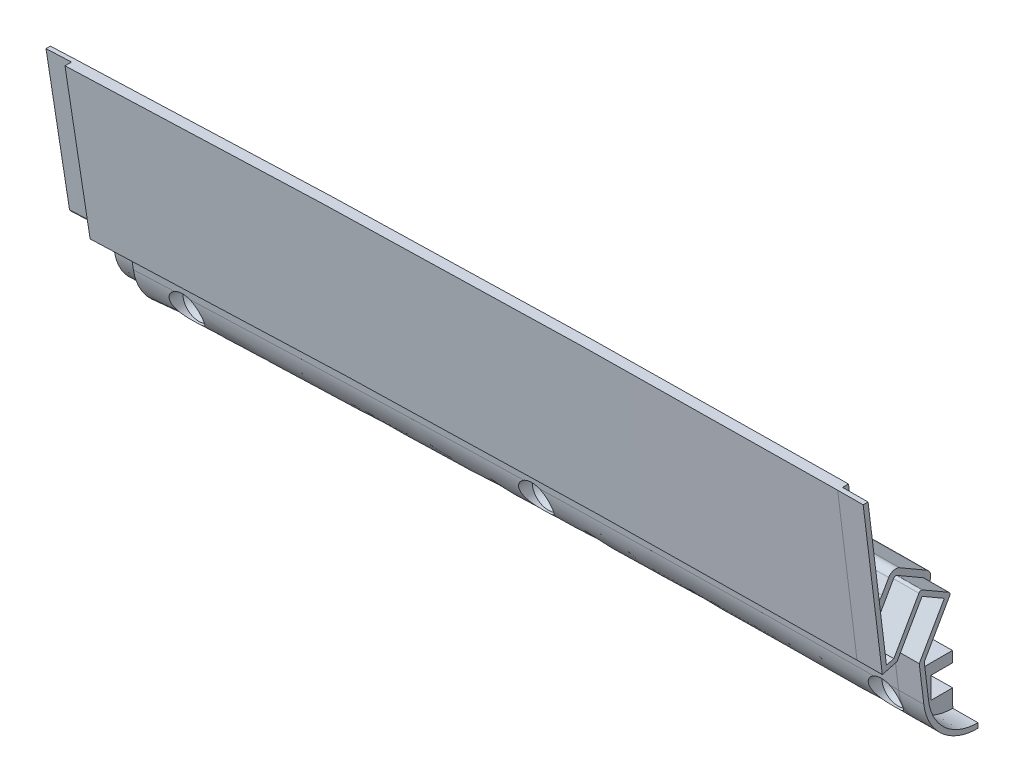
SolidWorks part; units mm, degrees
ref_plane "Front Plane" through (0, 0, 0) normal (0, 0, 1) x (1, 0, 0)
ref_plane "Top Plane" through (0, 0, 0) normal (0, 1, 0) x (1, 0, 0)
ref_plane "Right Plane" through (0, 0, 0) normal (1, 0, 0) x (0, 0, -1)
ref_plane "Plane3" through (-117.056, -3.871, 0) normal (0.9995, 0.0331, 0) x (0, 0, -1)
sketch "Sketch2" plane through (-117.056, -3.871, 0) normal (0.9995, 0.0331, 0) x (0, 0, -1)
  line L0 (-101.6, -41.1511) -> (-101.6, -45.9265)
  line L1 (-101.6, -41.1511) -> (-101.6, -45.9265)
  line L2 (-106.68, -45.9265) -> (-106.68, -50.6257)
  line L3 (-106.68, -45.9265) -> (-106.68, -50.6257)
  line L4 (-101.6, -50.6257) -> (-106.68, -50.6257)
  line L5 (-101.6, -50.6257) -> (-106.68, -50.6257)
  line L6 (-101.6, -50.6257) -> (-101.6, -56.1377)
  line L7 (-101.6, -50.6257) -> (-101.6, -56.1377)
  line L8 (-106.68, -45.9265) -> (-101.6, -45.9265)
  line L9 (-106.68, -45.9265) -> (-101.6, -45.9265)
  line L10 (-106.8705, -50.8162) -> (-108.9961, -53.9781) construction
  line L11 (-101.7905, -43.196) -> (-101.7905, -45.736)
  line L12 (-106.8705, -45.736) -> (-101.7905, -45.736)
  line L13 (-106.8705, -45.736) -> (-106.8705, -50.8162)
  line L14 (-101.7905, -50.8162) -> (-106.8705, -50.8162)
  line L15 (-101.7905, -50.8162) -> (-101.7905, -56.1377)
  line L16 (-101.7905, -43.196) -> (-101.6, -43.196)
  line L17 (-101.7905, -41.1511) -> (-101.7905, -45.736) construction
  line L18 (-120.8053, -33.0481) -> (-115.57, -36.0708)
  line L19 (-120.8053, -33.0481) -> (-115.57, -36.0708)
  line L20 (-109.601, -25.7318) -> (-114.8363, -22.709)
  line L21 (-109.601, -25.7318) -> (-114.8363, -22.709)
  line L22 (-114.8363, -22.709) -> (-120.8053, -33.0481)
  line L23 (-114.8363, -22.709) -> (-120.8053, -33.0481)
  line L24 (-115.57, -36.0708) -> (-109.601, -25.7318)
  line L25 (-115.57, -36.0708) -> (-109.601, -25.7318)
  line L26 (-115.57, -36.0708) -> (-114.523, -44.9291)
  line L28 (-118.1876, -34.5595) -> (-112.2186, -24.2204) construction
  line L29 (-114.6403, -39.5406) -> (-107.0838, -26.4518)
  line L30 (-107.7811, -23.8496) -> (-114.1162, -20.1918)
  line L31 (-116.7185, -20.8891) -> (-124.2749, -33.9778)
  line L33 (-106.1314, -24.8021) -> (-115.766, -19.2393) construction
  line L34 (-115.766, -19.2393) -> (-124.2749, -33.9778) construction
  line L35 (-114.6403, -39.5406) -> (-106.1314, -24.8021) construction
  line L36 (-124.2749, -33.9778) -> (-114.6403, -39.5406) construction
  line L37 (-112.9486, -36.6103) -> (-112.1701, -43.196)
  line L38 (-124.2749, -33.9778) -> (-128.0422, -2.1051)
  line L39 (-128.0422, -2.1051) -> (-132.6063, -0.4439)
  line L40 (-50.8, 0.7495) -> (-2184.4, 0.7495)
  line L41 (-125.822, 0.7495) -> (-133.442, 0.7495)
  line L42 (-122.1519, -30.3004) -> (-125.822, 0.7495)
  arc A0 (-114.523, -44.9291) -> (-101.7905, -56.1377) centre (-101.9108, -43.4383) ccw
  arc A2 (-114.1162, -20.1918) -> (-116.7185, -20.8891) centre (-115.0687, -21.8416) ccw
  arc A3 (-107.0838, -26.4518) -> (-107.7811, -23.8496) centre (-108.7336, -25.4993) ccw
  arc A4 (-133.442, 0.7495) -> (-132.6063, -0.4439) centre (-132.172, 0.7495) ccw
  point P41 (-133.442, 0.7495)
  dimension "D2" = 25.4
  dimension "D6" = 1.905
  dimension "D8" = 2.54
  dimension "D4" = 2.54
  dimension "D5" = 2.54
  dimension "D7" = 2.54
  dimension "D9" = 2.54
  dimension "D10" = 20
  dimension "D11" = 7.62
  dimension "D12" = 3.81
  dimension "D3" = 0.1905
sketch "Sketch3" plane through (0, 0, 101.6) normal (0, 0, 1) x (1, 0, 0)
  arc A0 (622.1039, -83.1998) -> (-622.1039, -83.1998) centre (0, -4954.4862) ccw construction
  arc A1 (622.1039, -83.1998) -> (-622.1039, -83.1998) centre (0, -4954.4862) ccw
sketch "Sketch4" plane through (-117.3306, 4.4304, 1117.6) normal (0.9995, 0.0331, 0) x (0, 0, -1)
  line L29 (1009.8189, -32.1556) -> (1003.4838, -28.4978) construction
  line L32 (1000.8815, -29.1951) -> (993.3251, -42.2838) construction
  line L35 (993.3251, -42.2838) -> (989.5578, -10.4111) construction
  line L50 (995.4481, -38.6064) -> (991.778, -7.5565) construction
  line L51 (1002.03, -44.3768) -> (1003.077, -53.235) construction
  line L52 (1015.8095, -59.1222) -> (1015.8095, -64.4437) construction
  line L53 (1015.8095, -59.1222) -> (1010.7295, -59.1222) construction
  line L54 (1010.7295, -54.042) -> (1010.7295, -59.1222) construction
  line L55 (1010.7295, -54.042) -> (1015.8095, -54.042) construction
  line L56 (1015.8095, -51.502) -> (1015.8095, -54.042) construction
  line L57 (1015.8095, -51.502) -> (1016, -51.502) construction
  line L58 (1004.6514, -44.9163) -> (1005.4299, -51.502) construction
  line L60 (1002.7637, -31.015) -> (996.7947, -41.3541) construction
  line L61 (1007.999, -34.0377) -> (1002.7637, -31.015) construction
  line L62 (1002.03, -44.3768) -> (1007.999, -34.0377) construction
  line L64 (991.5295, -5.4538) -> (988.9718, -5.4538)
  line L69 (1009.8189, -32.1556) -> (1003.4838, -28.4978)
  line L70 (1000.8815, -29.1951) -> (999.2724, -31.9822)
  line L71 (993.3251, -42.2838) -> (988.9718, -5.4538)
  line L74 (994.5502, -31.0104) -> (991.5295, -5.4538)
  line L75 (1002.03, -44.3768) -> (1003.077, -53.235)
  line L76 (1015.8095, -59.1222) -> (1015.8095, -64.4437)
  line L77 (1015.8095, -59.1222) -> (1010.7295, -59.1222)
  line L78 (1010.7295, -54.042) -> (1010.7295, -59.1222)
  line L79 (1010.7295, -54.042) -> (1015.8095, -54.042)
  line L80 (1015.8095, -51.502) -> (1015.8095, -54.042)
  line L81 (1015.8095, -51.502) -> (1007.6873, -51.502)
  line L82 (1004.7505, -45.7539) -> (1005.1649, -49.2601)
  line L84 (1002.7637, -31.015) -> (996.7947, -41.3541)
  line L85 (1007.999, -34.0377) -> (1002.7637, -31.015)
  line L86 (1002.03, -44.3768) -> (1007.999, -34.0377)
  line L87 (996.7947, -41.3541) -> (993.3251, -42.2838)
  line L88 (1005.0732, -44.1858) -> (1010.5162, -34.7578)
  arc A8 (1010.5162, -34.7578) -> (1009.8189, -32.1556) centre (1008.8664, -33.8053) ccw construction
  arc A9 (1003.4838, -28.4978) -> (1000.8815, -29.1951) centre (1002.5313, -30.1476) ccw construction
  arc A11 (1003.077, -53.235) -> (1015.8095, -64.4437) centre (1015.6892, -51.7443) ccw construction
  arc A12 (1010.5162, -34.7578) -> (1009.8189, -32.1556) centre (1008.8664, -33.8053) ccw
  arc A13 (1003.4838, -28.4978) -> (1000.8815, -29.1951) centre (1002.5313, -30.1476) ccw
  arc A15 (1003.077, -53.235) -> (1015.8095, -64.4437) centre (1015.6892, -51.7443) ccw
  arc A16 (1005.1649, -49.2601) -> (1007.6873, -51.502) centre (1007.6873, -48.962) ccw
  arc A17 (1004.7505, -45.7539) -> (1005.0732, -44.1858) centre (1007.2729, -45.4558) cw
  arc A18 (994.5502, -31.0104) -> (999.2724, -31.9822) centre (997.0727, -30.7122) ccw
  dimension "D2" = 2.54
  dimension "D1" = 36.83
sweep "Sweep3" add profiles "Sketch4" path "Sketch3"
sketch "Sketch5" plane through (0, 0, 101.7905) normal (0, 0, -1) x (-1, 0, 0)
  line L0 (211.6509, -4.1577) -> (0, -4954.4862) construction
  line L1 (0, -4954.4862) -> (29.1844, -1.5588) construction
  line L2 (117.0808, -1.0187) -> (0, -4954.4862) construction
  arc A1 (628.0925, -39.606) -> (-627.2635, -39.5001) centre (0, -4954.4862) ccw construction
  point P2 (0, 0)
  point P4 (36.4599, -7.8244)
  point P16 (117.0808, -1.0187)
ref_plane "Plane1" through (-211.4422, -9.0402, 0) normal (-0.9991, -0.0427, 0) x (0.0427, -0.9991, 0)
ref_plane "Plane2" through (-29.1926, -0.172, 0) normal (1, 0.0059, 0) x (-0.0059, 1, 0)
other "SurfaceCut1"
other "SurfaceCut2"
sketch "Sketch8" plane through (-117.056, -3.871, 0) normal (0.9995, 0.0331, 0) x (0, 0, -1)
  line L0 (-106.8705, -50.8162) -> (-106.8705, -45.736)
  line L1 (-106.8705, -50.8162) -> (-106.8705, -45.736)
  line L2 (-106.8705, -48.2761) -> (-119.5705, -48.2761)
  line L3 (-119.5705, -48.2761) -> (-119.5705, -44.4661)
  line L4 (-119.5705, -44.4661) -> (-110.6805, -44.4661)
  line L5 (-110.6805, -44.4661) -> (-108.7755, -46.3711)
  line L6 (-108.7755, -46.3711) -> (-106.8705, -46.3711)
  line L7 (-119.5705, -48.2761) -> (-117.7248, -48.2761) construction
  dimension "D1" = 1.905
  dimension "D2" = 1.905
  dimension "D3" = 12.7
  dimension "D4" = 45
  dimension "D5" = 3.81
revolve "Cut-Revolve1" cut sketch "Sketch8" angle 360 about L7
sketch "Sketch9" plane through (0, 0, 106.8705) normal (0, 0, -1) x (-1, 0, 0)
  line L0 (198.0737, -52.2212) -> (197.8686, -57.297) construction
  line L1 (32.934, -48.3318) -> (32.8999, -53.4117) construction
  arc A1 (209.5755, -52.6994) -> (28.909, -48.3064) centre (0, -4954.4862) ccw construction
  arc A2 (209.3585, -57.7748) -> (28.879, -53.3863) centre (0, -4954.4862) ccw construction
  point P8 (197.9712, -54.7591)
  point P11 (0, -4954.4862)
  point P16 (115.4604, -52.1207)
  dimension "D1" = 82.55
  dimension "D2" = 82.55
sketch "Sketch10" plane through (0, 0, 106.8705) normal (0, 0, -1) x (-1, 0, 0)
  line L0 (32.934, -48.3318) -> (32.8999, -53.4117) construction
  point P0 (32.917, -50.8717)
  point P1 (197.9712, -54.7591)
pattern_sketch "Sketch-Pattern1" of "Cut-Revolve1" driven by "Sketch10"
sketch "Sketch12" plane through (0, 0, 101.7905) normal (0, 0, -1) x (-1, 0, 0)
  line L0 (28.9239, -45.7666) -> (0, -4954.4862) construction
  line L1 (0, -4954.4862) -> (22.9549, -45.7351) construction
  arc A1 (209.684, -50.1619) -> (28.9239, -45.7666) centre (0, -4954.4862) ccw construction
  arc A2 (28.9239, -45.7666) -> (22.9549, -45.7351) centre (0, -4954.4862) ccw
  dimension "D1" = 5.969
sketch "Sketch11" plane through (-29.1926, -0.172, 0) normal (1, 0.0059, 0) x (0, 0, -1)
  line L0 (-127.4772, 0.4508) -> (-123.2949, -34.9317)
  line L1 (-123.2949, -34.9317) -> (-121.5584, -34.4664)
  line L2 (-121.5584, -34.4664) -> (-115.5722, -24.0979)
  line L3 (-114.7047, -23.8655) -> (-108.5896, -27.3961)
  line L4 (-108.3571, -28.2635) -> (-114.3903, -38.7133)
  line L5 (-114.3903, -38.7133) -> (-113.3879, -47.1942)
  line L6 (-127.4931, 0.5849) -> (-123.2949, -34.9317) construction
  line L7 (-101.7905, -58.5366) -> (-101.7905, -57.3936)
  line L8 (-101.7905, -53.2152) -> (-101.7905, -58.5366) construction
  line L9 (-101.7905, -57.3936) -> (-101.8013, -57.3936)
  line L10 (-115.2547, -23.548) -> (-108.0396, -27.7136) construction
  line L11 (-108.0396, -27.7136) -> (-114.3903, -38.7133) construction
  line L12 (-121.5584, -34.4664) -> (-115.2547, -23.548) construction
  line L18 (-126.0705, 0.4508) -> (-128.6282, 0.4508)
  line L19 (-128.6282, 0.4508) -> (-124.2749, -36.3776)
  line L20 (-124.2749, -36.3776) -> (-120.8053, -35.448)
  line L21 (-120.8053, -35.448) -> (-114.8363, -25.1093)
  line L22 (-114.8363, -25.1093) -> (-109.601, -28.1319)
  line L23 (-109.601, -28.1319) -> (-115.57, -38.4706)
  line L24 (-115.57, -38.4706) -> (-114.523, -47.3284)
  line L25 (-101.7905, -58.5366) -> (-101.7905, -53.2152)
  line L26 (-101.7905, -53.2152) -> (-106.8705, -53.2152)
  line L27 (-106.8705, -53.2152) -> (-106.8705, -48.1353)
  line L28 (-106.8705, -48.1353) -> (-101.7905, -48.1353)
  line L29 (-101.7905, -48.1353) -> (-101.7905, -45.5954)
  line L30 (-101.7905, -45.5954) -> (-109.9127, -45.5954)
  line L31 (-112.4351, -43.3536) -> (-112.8495, -39.8476)
  line L32 (-112.5268, -38.2796) -> (-107.0838, -28.852)
  line L33 (-107.781, -26.2499) -> (-114.1162, -22.5923)
  line L34 (-116.7185, -23.2895) -> (-118.3276, -26.0765)
  line L35 (-123.0498, -25.1047) -> (-126.0705, 0.4508)
  line L36 (-127.4772, 0.4508) -> (-128.6282, 0.4508)
  line L37 (-128.6282, 0.4508) -> (-124.2749, -36.3776)
  line L38 (-124.2749, -36.3776) -> (-120.8053, -35.448)
  line L39 (-120.8053, -35.448) -> (-114.8363, -25.1093)
  line L40 (-114.8363, -25.1093) -> (-109.601, -28.1319)
  line L41 (-109.601, -28.1319) -> (-115.57, -38.4706)
  line L42 (-115.57, -38.4706) -> (-114.523, -47.3284)
  arc A0 (-108.5896, -27.3961) -> (-108.3571, -28.2635) centre (-108.9071, -27.946) cw
  arc A1 (-115.5722, -24.0979) -> (-114.7047, -23.8655) centre (-115.0222, -24.4154) cw
  arc A4 (-112.4351, -43.3536) -> (-109.9127, -45.5954) centre (-109.9127, -43.0554) ccw
  arc A5 (-112.5268, -38.2796) -> (-112.8495, -39.8476) centre (-110.3273, -39.5495) ccw
  arc A6 (-107.0838, -28.852) -> (-107.781, -26.2499) centre (-108.7335, -27.8995) ccw
  arc A7 (-114.1162, -22.5923) -> (-116.7185, -23.2895) centre (-115.0687, -24.2421) ccw
  spline S0 degree 1 poles (-113.3879, -47.1942) (-101.8013, -57.3936) knots 0 0 1 1 construction
  spline S1 degree 3 poles (-113.3879, -47.1942) (-113.3048, -47.897) (-113.0054, -49.297) (-111.9316, -51.8878) (-109.7159, -54.7112) (-106.0351, -56.912) (-103.2019, -57.4069) (-101.8013, -57.3936) knots 0 0 0 0 0.125 0.25 0.5 0.75 1 1 1 1
  spline S2 degree 3 poles (1806.7112, 500.6935) (415.3182, 185.4579) (-128.7728, 19.3396) (-114.2511, -48.8637) (-114.1523, -49.2411) (-113.8076, -50.3489) (-113.513, -51.0601) (-112.7943, -52.4279) (-112.3662, -53.0879) (-111.4114, -54.3004) (-110.8822, -54.8597) (-110.0099, -55.6273) (-109.7043, -55.8723) (-109.0766, -56.3297) (-108.7542, -56.5426) (-107.762, -57.1353) (-107.0674, -57.4692) (-105.9744, -57.8757) (-105.6018, -57.9951) (-104.8546, -58.1973) (-104.4782, -58.2809) (-51.6561, -67.5201) (53.4105, 251.0315) (369.459, 1883.5165) knots -11.048432 -11.048432 -11.048432 -11.048432 0.0625 0.0625 0.125 0.125 0.25 0.25 0.375 0.375 0.5 0.5 0.5625 0.5625 0.625 0.625 0.75 0.75 0.8125 0.8125 0.875 0.875 9.519326 9.519326 9.519326 9.519326 only from (-114.523, -47.3284) to (-101.7905, -58.5366)
  spline S3 degree 3 poles (-966.8365, -555.252) (-146.5253, 43.3785) (-110.7563, -19.4167) (-119.0219, -26.8692) (-119.2485, -27.0168) (-119.7291, -27.2321) (-119.9898, -27.3029) (-120.3827, -27.3458) (-120.5144, -27.3499) (-120.779, -27.3374) (-120.9121, -27.3206) (-121.1705, -27.2672) (-121.297, -27.2307) (-121.5443, -27.1377) (-121.6661, -27.0808) (-121.896, -26.9503) (-122.0051, -26.8766) (-122.2115, -26.7124) (-122.3097, -26.621) (-122.5785, -26.3279) (-122.7254, -26.1069) (-131.5662, -6.8246) (104.7841, 84.3765) (817.0786, 315.713) knots -5.03449 -5.03449 -5.03449 -5.03449 0.125 0.125 0.25 0.25 0.375 0.375 0.4375 0.4375 0.5 0.5 0.5625 0.5625 0.625 0.625 0.6875 0.6875 0.75 0.75 0.875 0.875 10.718854 10.718854 10.718854 10.718854 only from (-118.3276, -26.0765) to (-123.0498, -25.1047)
  spline S4 degree 3 poles (-114.523, -47.3284) (-114.4771, -47.7161) (-114.4136, -48.1007) (-114.2511, -48.8637) (-114.1523, -49.2411) (-113.8076, -50.3489) (-113.513, -51.0601) (-112.7943, -52.4279) (-112.3662, -53.0879) (-111.4114, -54.3004) (-110.8822, -54.8597) (-110.0099, -55.6273) (-109.7043, -55.8723) (-109.0766, -56.3297) (-108.7542, -56.5426) (-107.762, -57.1353) (-107.0674, -57.4692) (-105.9744, -57.8757) (-105.6018, -57.9951) (-104.8546, -58.1973) (-104.4782, -58.2809) (-103.3407, -58.4798) (-102.5713, -58.544) (-101.7905, -58.5366) knots 0 0 0 0 0.0625 0.0625 0.125 0.125 0.25 0.25 0.375 0.375 0.5 0.5 0.5625 0.5625 0.625 0.625 0.75 0.75 0.8125 0.8125 0.875 0.875 1 1 1 1
  dimension "D3" = 0.635
  dimension "D1" = 0
  dimension "D2" = 1.143
sweep "Sweep4" add profiles "Sketch11" path "Sketch12"
sketch "Sketch14" plane through (-211.4422, -9.0402, 0) normal (-0.9991, -0.0427, 0) x (0, 0, 1)
  line L0 (113.0095, -42.7133) -> (113.9971, -34.3581)
  line L1 (113.9971, -34.3581) -> (107.5192, -23.138)
  line L2 (107.5192, -23.138) -> (115.3941, -18.5914)
  line L3 (115.3941, -18.5914) -> (121.8095, -29.7031)
  line L4 (121.8095, -29.7031) -> (122.9682, -30.0136)
  line L5 (122.9682, -30.0136) -> (127.1147, 5.0658)
  line L18 (128.6282, 4.8869) -> (126.0705, 4.8869)
  line L19 (126.0705, 4.8869) -> (123.0498, -20.6686)
  line L20 (118.3276, -21.6403) -> (116.7185, -18.8534)
  line L21 (114.1162, -18.1561) -> (107.7811, -21.8137)
  line L22 (107.0838, -24.4158) -> (112.5268, -33.8434)
  line L23 (112.8495, -35.4115) -> (112.4351, -38.9175)
  line L24 (109.9127, -41.1592) -> (101.7905, -41.1592)
  line L25 (101.7905, -41.1592) -> (101.7905, -43.6991)
  line L26 (101.7905, -43.6991) -> (106.8705, -43.6991)
  line L27 (106.8705, -43.6991) -> (106.8705, -48.7791)
  line L28 (106.8705, -48.7791) -> (101.7905, -48.7791)
  line L29 (101.7905, -48.7791) -> (101.7905, -54.1004)
  line L30 (114.523, -42.8922) -> (115.57, -34.0344)
  line L31 (115.57, -34.0344) -> (109.601, -23.6958)
  line L32 (109.601, -23.6958) -> (114.8363, -20.6732)
  line L33 (114.8363, -20.6732) -> (120.8053, -31.0118)
  line L34 (120.8053, -31.0118) -> (124.2749, -31.9414)
  line L35 (124.2749, -31.9414) -> (128.6282, 4.8869)
  line L36 (128.6282, 4.8869) -> (126.0705, 4.8869)
  line L37 (126.0705, 4.8869) -> (123.0498, -20.6686)
  line L38 (118.3276, -21.6403) -> (116.7185, -18.8534)
  line L39 (114.1162, -18.1561) -> (107.7811, -21.8137)
  line L40 (107.0838, -24.4158) -> (112.5268, -33.8434)
  line L41 (112.8495, -35.4115) -> (112.4351, -38.9175)
  line L42 (109.9127, -41.1592) -> (101.7905, -41.1592)
  line L43 (101.7905, -41.1592) -> (101.7905, -43.6991)
  line L44 (101.7905, -43.6991) -> (106.8705, -43.6991)
  line L45 (106.8705, -43.6991) -> (106.8705, -48.7791)
  line L46 (106.8705, -48.7791) -> (101.7905, -48.7791)
  line L47 (101.7905, -48.7791) -> (101.7905, -54.1004)
  line L48 (114.523, -42.8922) -> (115.57, -34.0344)
  line L49 (115.57, -34.0344) -> (109.601, -23.6958)
  line L50 (109.601, -23.6958) -> (114.8363, -20.6732)
  line L51 (114.8363, -20.6732) -> (120.8053, -31.0118)
  line L52 (120.8053, -31.0118) -> (124.2749, -31.9414)
  line L53 (124.2749, -31.9414) -> (128.6282, 4.8869)
  arc A4 (116.7185, -18.8534) -> (114.1162, -18.1561) centre (115.0687, -19.8059) ccw
  arc A5 (107.7811, -21.8137) -> (107.0838, -24.4158) centre (108.7335, -23.4634) ccw
  arc A6 (112.8495, -35.4115) -> (112.5268, -33.8434) centre (110.3273, -35.1133) ccw
  arc A7 (109.9127, -41.1592) -> (112.4351, -38.9175) centre (109.9127, -38.6193) ccw
  arc A8 (116.7185, -18.8534) -> (114.1162, -18.1561) centre (115.0687, -19.8059) ccw
  arc A9 (107.7811, -21.8137) -> (107.0838, -24.4158) centre (108.7335, -23.4634) ccw
  arc A10 (112.8495, -35.4115) -> (112.5268, -33.8434) centre (110.3273, -35.1133) ccw
  arc A11 (109.9127, -41.1592) -> (112.4351, -38.9175) centre (109.9127, -38.6193) ccw
  spline S0 degree 1 poles (101.8049, -52.5765) (113.0095, -42.7133) knots 0 0 1 1 construction
  spline S1 degree 3 poles (101.8049, -52.5765) (102.4893, -52.583) (103.8689, -52.4674) (106.4858, -51.7551) (109.4658, -49.9761) (112.0284, -46.7154) (112.8505, -44.0584) (113.0095, -42.7133) knots 0 0 0 0 0.125 0.25 0.5 0.75 1 1 1 1
  spline S2 degree 3 poles (-1420.2451, -2589.1907) (7.5348, 76.4537) (129.3579, -7.252) (122.7249, -21.671) (122.575, -21.8961) (122.2185, -22.2837) (122.0069, -22.4517) (121.6628, -22.6462) (121.5435, -22.702) (121.2955, -22.795) (121.1665, -22.8321) (120.908, -22.8851) (120.7774, -22.9014) (120.5134, -22.9137) (120.3791, -22.9094) (120.1163, -22.8803) (119.987, -22.8557) (119.7325, -22.7864) (119.6063, -22.7412) (119.2436, -22.578) (119.0214, -22.433) (93.7379, 0.421) (581.1886, 448.0858) (2362.312, 1968.4478) knots -7.286241 -7.286241 -7.286241 -7.286241 0.125 0.125 0.25 0.25 0.375 0.375 0.4375 0.4375 0.5 0.5 0.5625 0.5625 0.625 0.625 0.6875 0.6875 0.75 0.75 0.875 0.875 16.766809 16.766809 16.766809 16.766809 only from (123.0498, -20.6686) to (118.3276, -21.6403)
  spline S3 degree 3 poles (-288.3388, 2916.9987) (-102.777, 757.3692) (19.5454, -60.9671) (103.3479, -54.0254) (103.7348, -53.9753) (104.8774, -53.7738) (105.6202, -53.5717) (107.068, -53.0324) (107.777, -52.6914) (109.1008, -51.8981) (109.7227, -51.4442) (110.5948, -50.6762) (110.8766, -50.4042) (111.4099, -49.8396) (111.662, -49.5468) (112.3757, -48.6378) (112.795, -47.9912) (113.3369, -46.9586) (113.5026, -46.6041) (113.7979, -45.8886) (113.9285, -45.5258) (132.5439, 14.5864) (-288.4354, 203.7302) (-2703.1014, 979.8882) knots -13.349036 -13.349036 -13.349036 -13.349036 0.0625 0.0625 0.125 0.125 0.25 0.25 0.375 0.375 0.5 0.5 0.5625 0.5625 0.625 0.625 0.75 0.75 0.8125 0.8125 0.875 0.875 11.030088 11.030088 11.030088 11.030088 only from (101.7905, -54.1004) to (114.523, -42.8922)
  spline S4 degree 3 poles (123.0498, -20.6686) (123.0184, -20.9338) (122.9449, -21.1927) (122.7249, -21.671) (122.575, -21.8961) (122.2185, -22.2837) (122.0069, -22.4517) (121.6628, -22.6462) (121.5435, -22.702) (121.2955, -22.795) (121.1665, -22.8321) (120.908, -22.8851) (120.7774, -22.9014) (120.5134, -22.9137) (120.3791, -22.9094) (120.1163, -22.8803) (119.987, -22.8557) (119.7325, -22.7864) (119.6063, -22.7412) (119.2436, -22.578) (119.0214, -22.433) (118.6267, -22.0763) (118.4611, -21.8716) (118.3276, -21.6403) knots 0 0 0 0 0.125 0.125 0.25 0.25 0.375 0.375 0.4375 0.4375 0.5 0.5 0.5625 0.5625 0.625 0.625 0.6875 0.6875 0.75 0.75 0.875 0.875 1 1 1 1
  spline S5 degree 3 poles (101.7905, -54.1004) (102.1809, -54.1041) (102.5705, -54.0898) (103.3479, -54.0254) (103.7348, -53.9753) (104.8774, -53.7738) (105.6202, -53.5717) (107.068, -53.0324) (107.777, -52.6914) (109.1008, -51.8981) (109.7227, -51.4442) (110.5948, -50.6762) (110.8766, -50.4042) (111.4099, -49.8396) (111.662, -49.5468) (112.3757, -48.6378) (112.795, -47.9912) (113.3369, -46.9586) (113.5026, -46.6041) (113.7979, -45.8886) (113.9285, -45.5258) (114.2702, -44.4227) (114.4313, -43.6677) (114.523, -42.8922) knots 0 0 0 0 0.0625 0.0625 0.125 0.125 0.25 0.25 0.375 0.375 0.5 0.5 0.5625 0.5625 0.625 0.625 0.75 0.75 0.8125 0.8125 0.875 0.875 1 1 1 1
  dimension "D1" = 0
  dimension "D2" = 1.524
sketch "Sketch15" plane through (-211.4422, -9.0402, 0) normal (-0.9991, -0.0427, 0) x (0, 0, 1)
  line L0 (113.0095, -42.7133) -> (113.9971, -34.3581) construction
  line L1 (113.9971, -34.3581) -> (107.5192, -23.138) construction
  line L2 (107.5192, -23.138) -> (115.3941, -18.5914) construction
  line L3 (115.3941, -18.5914) -> (121.8095, -29.7031) construction
  line L4 (121.8095, -29.7031) -> (122.9682, -30.0136) construction
  line L5 (122.9682, -30.0136) -> (127.1147, 5.0658) construction
  line L6 (113.0095, -42.7133) -> (113.9724, -34.5675)
  line L7 (113.8917, -34.1755) -> (107.5192, -23.138)
  line L8 (107.5192, -23.138) -> (115.3941, -18.5914)
  line L9 (115.3941, -18.5914) -> (121.678, -29.4753)
  line L10 (122.0636, -29.7712) -> (122.2594, -29.8237)
  line L11 (123.0543, -29.2848) -> (127.0936, 4.8869)
  line L12 (101.7905, -48.7791) -> (101.7905, -54.1004) construction
  line L13 (101.7905, -48.7791) -> (101.7905, -52.5765)
  line L14 (101.8049, -52.5765) -> (101.7905, -52.5765)
  line L18 (124.2749, -31.9414) -> (128.6282, 4.8869)
  line L19 (128.6282, 4.8869) -> (126.0705, 4.8869)
  line L20 (126.0705, 4.8869) -> (123.0498, -20.6686)
  line L21 (118.3276, -21.6403) -> (116.7185, -18.8534)
  line L22 (114.1162, -18.1561) -> (107.7811, -21.8137)
  line L23 (107.0838, -24.4158) -> (112.5268, -33.8434)
  line L24 (112.8495, -35.4115) -> (112.4351, -38.9175)
  line L25 (109.9127, -41.1592) -> (101.7905, -41.1592)
  line L26 (101.7905, -41.1592) -> (101.7905, -43.6991)
  line L27 (101.7905, -43.6991) -> (106.8705, -43.6991)
  line L28 (106.8705, -43.6991) -> (106.8705, -48.7791)
  line L29 (106.8705, -48.7791) -> (101.7905, -48.7791)
  line L30 (101.7905, -48.7791) -> (101.7905, -54.1004)
  line L31 (114.523, -42.8922) -> (115.57, -34.0344)
  line L32 (115.57, -34.0344) -> (109.601, -23.6958)
  line L33 (109.601, -23.6958) -> (114.8363, -20.6732)
  line L34 (114.8363, -20.6732) -> (120.8053, -31.0118)
  line L35 (120.8053, -31.0118) -> (124.2749, -31.9414)
  line L37 (127.0936, 4.8869) -> (126.0705, 4.8869)
  line L38 (126.0705, 4.8869) -> (123.0498, -20.6686)
  line L39 (118.3276, -21.6403) -> (116.7185, -18.8534)
  line L40 (114.1162, -18.1561) -> (107.7811, -21.8137)
  line L41 (107.0838, -24.4158) -> (112.5268, -33.8434)
  line L42 (112.8495, -35.4115) -> (112.4351, -38.9175)
  line L43 (109.9127, -41.1592) -> (101.7905, -41.1592)
  line L44 (101.7905, -41.1592) -> (101.7905, -43.6991)
  line L45 (101.7905, -43.6991) -> (106.8705, -43.6991)
  line L46 (106.8705, -43.6991) -> (106.8705, -48.7791)
  line L47 (106.8705, -48.7791) -> (101.7905, -48.7791)
  arc A0 (113.9724, -34.5675) -> (113.8917, -34.1755) centre (113.3418, -34.493) ccw
  arc A1 (121.678, -29.4753) -> (122.0636, -29.7712) centre (122.2279, -29.1578) ccw
  arc A2 (122.2594, -29.8237) -> (123.0543, -29.2848) centre (122.4237, -29.2103) ccw
  arc A4 (116.7185, -18.8534) -> (114.1162, -18.1561) centre (115.0687, -19.8059) ccw
  arc A5 (107.7811, -21.8137) -> (107.0838, -24.4158) centre (108.7335, -23.4634) ccw
  arc A6 (112.8495, -35.4115) -> (112.5268, -33.8434) centre (110.3273, -35.1133) ccw
  arc A7 (109.9127, -41.1592) -> (112.4351, -38.9175) centre (109.9127, -38.6193) ccw
  arc A8 (116.7185, -18.8534) -> (114.1162, -18.1561) centre (115.0687, -19.8059) ccw
  arc A9 (107.7811, -21.8137) -> (107.0838, -24.4158) centre (108.7335, -23.4634) ccw
  arc A10 (112.8495, -35.4115) -> (112.5268, -33.8434) centre (110.3273, -35.1133) ccw
  arc A11 (109.9127, -41.1592) -> (112.4351, -38.9175) centre (109.9127, -38.6193) ccw
  spline S0 degree 3 poles (1969.6766, 654.3437) (8.5109, 56.766) (75.3403, -60.2329) (106.4858, -51.7551) (109.4658, -49.9761) (134.2797, -18.4018) (-16.091, 107.1074) (-926.156, -1745.3361) knots -5.450838 -5.450838 -5.450838 -5.450838 0.125 0.25 0.5 0.75 7.512309 7.512309 7.512309 7.512309 only from (101.8049, -52.5765) to (113.0095, -42.7133) construction
  spline S1 degree 3 poles (101.8049, -52.5765) (102.4893, -52.583) (103.8689, -52.4674) (106.4858, -51.7551) (109.4658, -49.9761) (112.0284, -46.7154) (112.8505, -44.0584) (113.0095, -42.7133) knots 0 0 0 0 0.125 0.25 0.5 0.75 1 1 1 1
  spline S2 degree 3 poles (-1420.2451, -2589.1907) (7.5348, 76.4537) (129.3579, -7.252) (122.7249, -21.671) (122.575, -21.8961) (122.2185, -22.2837) (122.0069, -22.4517) (121.6628, -22.6462) (121.5435, -22.702) (121.2955, -22.795) (121.1665, -22.8321) (120.908, -22.8851) (120.7774, -22.9014) (120.5134, -22.9137) (120.3791, -22.9094) (120.1163, -22.8803) (119.987, -22.8557) (119.7325, -22.7864) (119.6063, -22.7412) (119.2436, -22.578) (119.0214, -22.433) (93.7379, 0.421) (581.1886, 448.0858) (2362.312, 1968.4478) knots -7.286241 -7.286241 -7.286241 -7.286241 0.125 0.125 0.25 0.25 0.375 0.375 0.4375 0.4375 0.5 0.5 0.5625 0.5625 0.625 0.625 0.6875 0.6875 0.75 0.75 0.875 0.875 16.766809 16.766809 16.766809 16.766809 only from (123.0498, -20.6686) to (118.3276, -21.6403)
  spline S3 degree 3 poles (-93.3253, 926.6784) (-10.5613, 232.0775) (53.1389, -58.1844) (103.3479, -54.0254) (103.7348, -53.9753) (104.8774, -53.7738) (105.6202, -53.5717) (107.068, -53.0324) (107.777, -52.6914) (109.1008, -51.8981) (109.7227, -51.4442) (110.5948, -50.6762) (110.8766, -50.4042) (111.4099, -49.8396) (111.662, -49.5468) (112.3757, -48.6378) (112.795, -47.9912) (113.3369, -46.9586) (113.5026, -46.6041) (113.7979, -45.8886) (113.9285, -45.5258) (125.9187, -6.8076) (-43.2917, 84.8615) (-804.6708, 350.8867) knots -7.947776 -7.947776 -7.947776 -7.947776 0.0625 0.0625 0.125 0.125 0.25 0.25 0.375 0.375 0.5 0.5 0.5625 0.5625 0.625 0.625 0.75 0.75 0.8125 0.8125 0.875 0.875 7.39364 7.39364 7.39364 7.39364 only from (101.7905, -54.1004) to (114.523, -42.8922)
  spline S4 degree 3 poles (123.0498, -20.6686) (123.0184, -20.9338) (122.9449, -21.1927) (122.7249, -21.671) (122.575, -21.8961) (122.2185, -22.2837) (122.0069, -22.4517) (121.6628, -22.6462) (121.5435, -22.702) (121.2955, -22.795) (121.1665, -22.8321) (120.908, -22.8851) (120.7774, -22.9014) (120.5134, -22.9137) (120.3791, -22.9094) (120.1163, -22.8803) (119.987, -22.8557) (119.7325, -22.7864) (119.6063, -22.7412) (119.2436, -22.578) (119.0214, -22.433) (118.6267, -22.0763) (118.4611, -21.8716) (118.3276, -21.6403) knots 0 0 0 0 0.125 0.125 0.25 0.25 0.375 0.375 0.4375 0.4375 0.5 0.5 0.5625 0.5625 0.625 0.625 0.6875 0.6875 0.75 0.75 0.875 0.875 1 1 1 1
  dimension "D2" = 0.635
  dimension "D1" = 0
sketch "Sketch16" plane through (0, 0, 101.7905) normal (0, 0, -1) x (-1, 0, 0)
  arc A0 (215.6474, -50.4205) -> (209.684, -50.1619) centre (0, -4954.4862) ccw
  arc A1 (209.684, -50.1619) -> (28.9239, -45.7666) centre (0, -4954.4862) ccw construction
  dimension "D1" = 5.969
sweep "Sweep5" add profiles "Sketch15" path "Sketch16"
